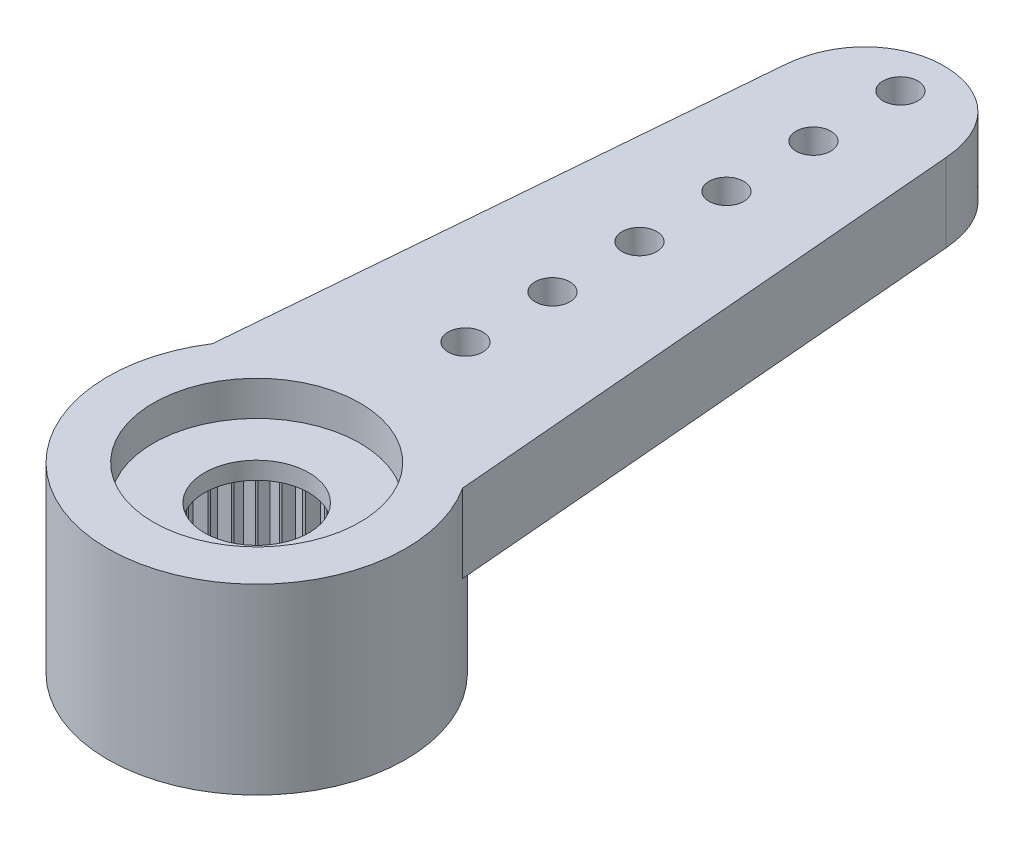
SolidWorks part; units mm, degrees
ref_plane "Front Plane" through (0, 0, 0) normal (0, 0, 1) x (1, 0, 0)
ref_plane "Top Plane" through (0, 0, 0) normal (0, 1, 0) x (1, 0, 0)
ref_plane "Right Plane" through (0, 0, 0) normal (1, 0, 0) x (0, 0, -1)
sketch "Sketch1" plane through (0, 0, 0) normal (0, 1, 0) x (1, 0, 0)
  circle A0 centre (0, 0) radius 3.425
  dimension "D1" = 6.85
extrude "HUB" add sketch "Sketch1" along normal blind 2.4
sketch "Sketch2" plane through (0, 2.4, 0) normal (0, 1, 0) x (1, 0, 0)
  line L0 (0, 0) -> (0, 16.2723) construction
  line L1 (-2.649, 14) -> (2.7333, 14) construction
  line L2 (-5.1175, 1.8615) -> (4.9374, 1.8615) construction
  line L3 (-2.875, 1.8615) -> (-1.85, 14)
  line L4 (2.875, 1.8615) -> (1.85, 14)
  line L5 (-1.7717, 14.9268) -> (-1.9284, 13.0721) construction
  line L6 (1.9338, 13.0078) -> (1.7662, 14.9922) construction
  line L7 (0.7058, 15.8) -> (-0.7062, 15.8) construction
  circle A0 centre (0, 0) radius 3.425 construction
  circle A1 centre (0, 14.8) radius 0.4
  circle A2 centre (0, 12.8) radius 0.4
  circle A3 centre (0, 10.8) radius 0.4
  circle A4 centre (0, 8.8) radius 0.4
  circle A5 centre (0, 6.8) radius 0.4
  circle A6 centre (0, 4.8) radius 0.4
  arc A7 (-2.875, 1.8615) -> (2.875, 1.8615) centre (0, 0) ccw
  spline S0 degree 3 poles (-1.85, 14) (-1.7619, 15.0433) (-0.8823, 15.8096) (0.8824, 15.8024) (1.7557, 15.1162) (1.85, 14) knots 0 0 0 0 0.45 0.55 1 1 1 1
  dimension "D4" = 0.8
  dimension "D1" = 14
  dimension "D2" = 3.7
  dimension "D3" = 5.75
  dimension "D5" = 1
  dimension "D6" = 6
extrude "Boss-Extrude2" add sketch "Sketch2" along normal blind 1.8
sketch "Sketch3" plane through (0, 4.2, 0) normal (0, 1, 0) x (1, 0, 0)
  circle A0 centre (0, 0) radius 2.375
  dimension "D1" = 4.75
extrude "Cut-Extrude1" cut sketch "Sketch3" against normal blind 0.8
sketch "Sketch4" plane through (0, 3.4, 0) normal (0, 1, 0) x (1, 0, 0)
  circle A0 centre (0, 0) radius 1.2
  dimension "D1" = 2.4
extrude "Cut-Extrude2" cut sketch "Sketch4" against normal through all
sketch "Sketch5" plane through (0, 0, 0) normal (0, -1, 0) x (1, 0, 0)
  line L0 (0, 0) -> (0, 4.9771) construction
  line L1 (0, 2.45) -> (-0.1734, 2.2433)
  line L2 (0, 2.45) -> (0.1734, 2.2433)
  circle A0 centre (0, 0) radius 2.25 construction
  arc A1 (-0.1734, 2.2433) -> (0.1734, 2.2433) centre (0, 0) cw
  point P7 (0, 2.25)
  dimension "D1" = 4.5
  dimension "D2" = 80
  dimension "D3" = 0.2
extrude "Cut-Extrude3" cut sketch "Sketch5" against normal blind 3 contours L1 A1 L2
pattern_circular "CirPattern1" count 36 over 360 about axis through (0, 0, 0) along (0, 1, 0) of "Cut-Extrude3"
sketch "Sketch6" plane through (0, 0, 0) normal (0, -1, 0) x (1, 0, 0)
  circle A0 centre (0, 0) radius 2.25
extrude "Cut-Extrude4" cut sketch "Sketch6" against normal blind 3
